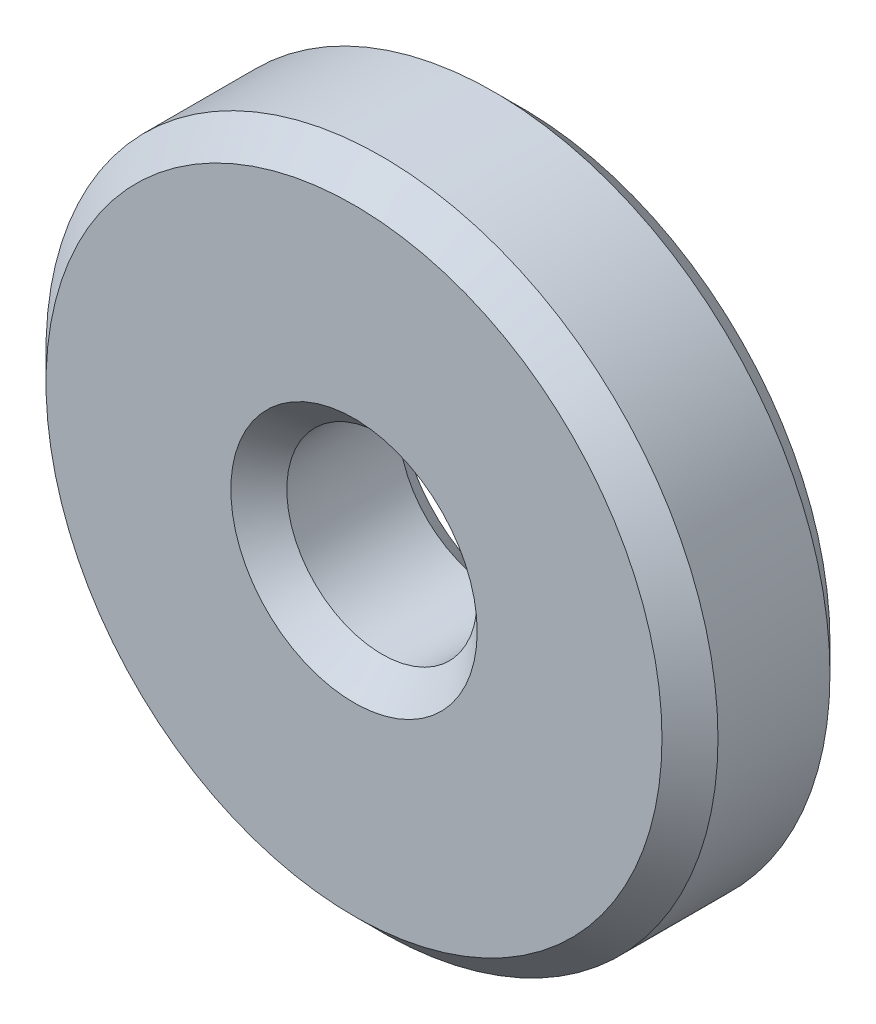
SolidWorks part; units mm, degrees
material "ABS"
ref_plane "Front Plane" through (0, 0, 0) normal (0, 0, 1) x (1, 0, 0)
ref_plane "Top Plane" through (0, 0, 0) normal (0, 1, 0) x (1, 0, 0)
ref_plane "Right Plane" through (0, 0, 0) normal (1, 0, 0) x (0, 0, -1)
sketch "Sketch1" plane through (0, 0, 0) normal (0, 0, 1) x (1, 0, 0)
  circle A0 centre (0, 0) radius 6
  circle A1 centre (0, 0) radius 1.7
  dimension "D1" = 12
  dimension "D2" = 3.4
extrude "Boss-Extrude1" add sketch "Sketch1" along normal blind 3
chamfer "Chamfer1" distance 0.5 angle 45 4 edges at (1.7, 0, 0) (6, 0, 0) (1.7, 0, 3) (6, 0, 3)
